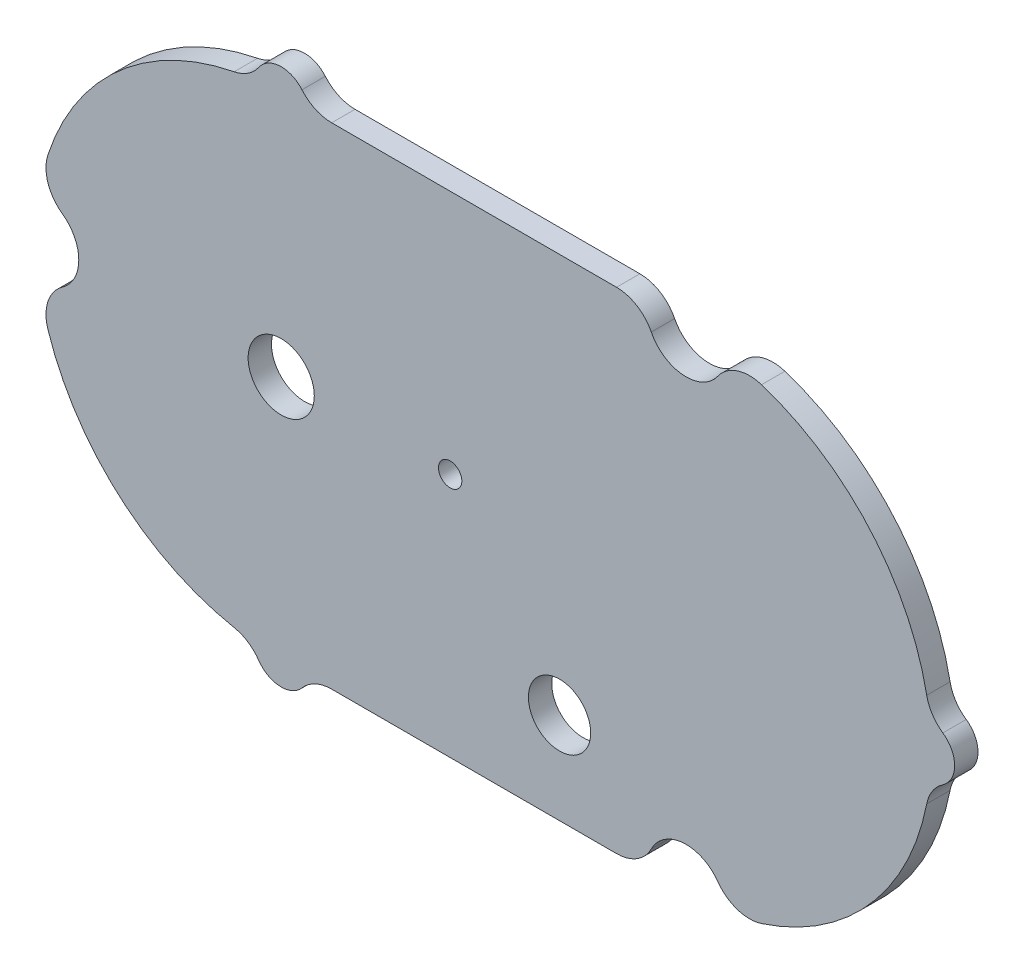
SolidWorks part; units mm, degrees
ref_plane "Front Plane" through (0, 0, 0) normal (0, 0, 1) x (1, 0, 0)
ref_plane "Top Plane" through (0, 0, 0) normal (0, 1, 0) x (1, 0, 0)
ref_plane "Right Plane" through (0, 0, 0) normal (1, 0, 0) x (0, 0, -1)
sketch "Sketch1" plane through (0, 0, 0) normal (0, 0, 1) x (1, 0, 0)
  line L0 (0, -31.5) -> (52, -31.5)
  line L5 (26, 0) -> (26, -31.5) construction
  line L21 (0, 31.5) -> (52, 31.5)
  line L23 (0, 0) -> (52, 0) construction
  line L24 (0, 0) -> (-31, 0) construction
  line L25 (52, 0) -> (83, 0) construction
  circle A6 centre (0, 0) radius 31.5 construction
  circle A17 centre (-31, 0) radius 1.45
  circle A18 centre (83, 0) radius 1.45
  circle A19 centre (0, 31) radius 1.45
  circle A20 centre (31, 0) radius 1.45 [skipped]
  circle A21 centre (0, -31) radius 1.45
  arc A24 (52, 31.5) -> (52, -31.5) centre (52, 0) cw
  arc A25 (0, 31.5) -> (0, -31.5) centre (0, 0) ccw
  circle A27 centre (0, 31) radius 3.5
  circle A28 centre (83, 0) radius 3.5
  circle A30 centre (0, -31) radius 3.5
  circle A31 centre (-31, 0) radius 5
  circle A32 centre (0, 0) radius 4.25
  circle A33 centre (21.7, 0) radius 1.5
  circle A34 centre (35.75, -19.75) radius 4
  circle A35 centre (52, -31) radius 5
  circle A36 centre (52, 31) radius 5
  point P18 (0, 0)
  point P27 (0, 0)
  point P28 (0, 0)
  point P59 (0, 0)
  point P69 (0, 0)
  dimension "D2" = 2.9
  dimension "D12" = 63
  dimension "D3" = 7
  dimension "D6" = 8.5
  dimension "D8" = 3
  dimension "D11" = 8
  dimension "D4" = 10
  dimension "D5" = 52
  dimension "D7" = 30.3
  dimension "D9" = 35.75
  dimension "D10" = 19.75
  dimension "D14" = 31
  dimension "D15" = 4
extrude "Boss-Extrude1" add sketch "Sketch1" against normal blind 3
fillet "Fillet1" radius 5 12 edges at (-31.1008, 4.999, -1.5) (-31.1008, -4.999, -1.5) (-3.4866, -31.3065, -1.5) (3.4641, -31.5, -1.5) (83.3065, -3.4866, -1.5) (83.3065, 3.4866, -1.5) (3.4641, 31.5, -1.5) (-3.4866, 31.3065, -1.5) (56.999, 31.1008, -1.5) (47.0251, 31.5, -1.5) (47.0251, -31.5, -1.5) (56.999, -31.1008, -1.5)
equation "\"speakerCenterDist\" = 40"
equation "\"speakerDiam\" = 50"
equation "\"boxInteriorDiam\" = 64"
equation "\"bearing_ext_diam\" = 16"
equation "\"bearing_int_diam\" = 5"
equation "\"bearing_thick\" = 5"
